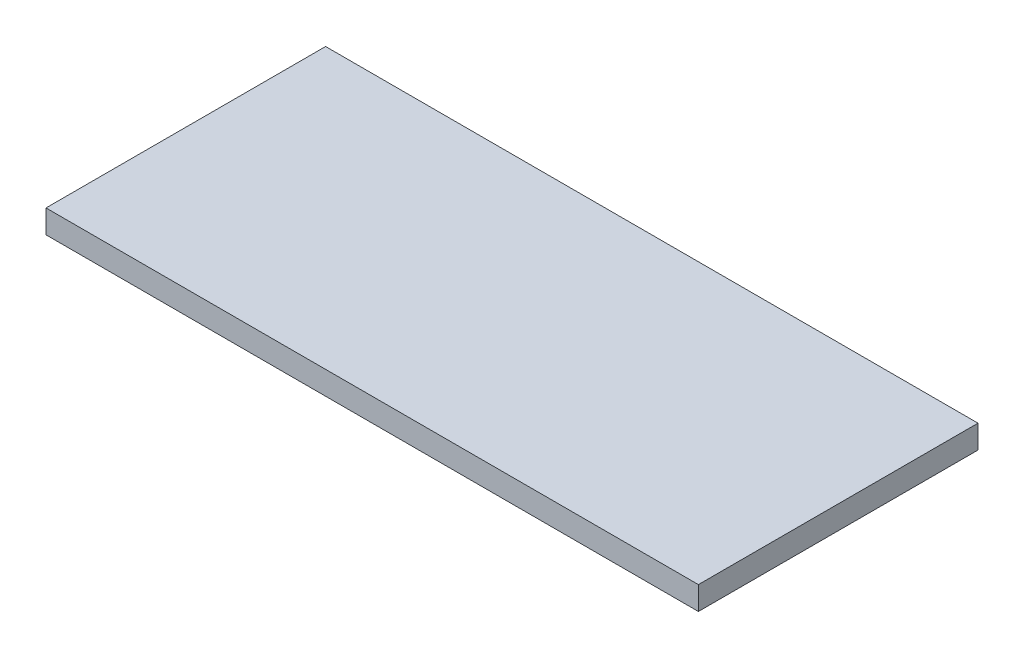
SolidWorks part; units mm, degrees
ref_plane "Front Plane" through (0, 0, 0) normal (0, 0, 1) x (1, 0, 0)
ref_plane "Top Plane" through (0, 0, 0) normal (0, 1, 0) x (1, 0, 0)
ref_plane "Right Plane" through (0, 0, 0) normal (1, 0, 0) x (0, 0, -1)
sketch "Sketch1" plane through (0, 0, 0) normal (0, 1, 0) x (1, 0, 0)
  line L1 (-44.45, 19.05) -> (44.45, 19.05)
  line L2 (-44.45, 19.05) -> (-44.45, -19.05)
  line L3 (-44.45, -19.05) -> (44.45, -19.05)
  line L4 (44.45, 19.05) -> (44.45, -19.05)
  line L5 (-44.45, 19.05) -> (44.45, -19.05) construction
  line L6 (-44.45, -19.05) -> (44.45, 19.05) construction
  point P0 (0, 0)
  dimension "D1" = 88.9
  dimension "D2" = 38.1
extrude "Boss-Extrude1" add sketch "Sketch1" along normal blind 3.175
